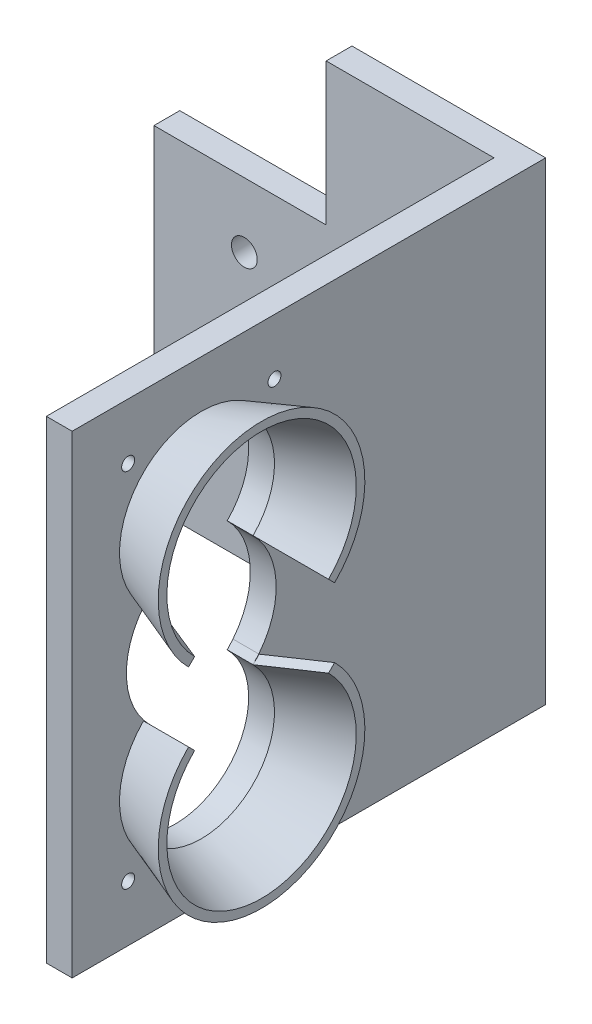
SolidWorks part; units mm, degrees
ref_plane "前视基准面" through (0, 0, 0) normal (0, 0, 1) x (1, 0, 0)
ref_plane "上视基准面" through (0, 0, 0) normal (0, 1, 0) x (1, 0, 0)
ref_plane "右视基准面" through (0, 0, 0) normal (1, 0, 0) x (0, 0, -1)
other "Configuration Table"
sketch "草图1" plane through (0, 0, 0) normal (0, 1, 0) x (1, 0, 0)
  line L0 (-16.6176, 27.2843) -> (25.8824, 27.2843)
  line L1 (25.8824, 27.2843) -> (25.8824, -27.7157)
  line L2 (25.8824, -27.7157) -> (22.8824, -27.7157)
  line L3 (22.8824, -27.7157) -> (22.8824, 24.2843)
  line L4 (22.8824, 24.2843) -> (-16.6176, 24.2843)
  line L5 (-16.6176, 24.2843) -> (-16.6176, 27.2843)
  dimension "D1" = 55
  dimension "D2" = 42.5
  dimension "D3" = 3
  dimension "D4" = 3
extrude "凸台-拉伸1" add sketch "草图1" along normal mid plane 55
ref_plane "基准面1" through (0, 0, -27.2843) normal (0, 0, -1) x (-1, 0, 0)
sketch "草图2" plane through (0, 0, -27.2843) normal (0, 0, -1) x (-1, 0, 0)
  line L0 (4.6176, -3.5) -> (-12.3824, -3.5)
  line L1 (-25.8824, 27.5) -> (-25.8824, -27.5) construction
  line L2 (16.6176, 27.5) -> (16.6176, -27.5) construction
  line L3 (-25.8824, 27.5) -> (16.6176, 27.5) construction
  line L4 (16.6176, -11) -> (-3.3824, -11)
  line L5 (-3.3824, -11) -> (-3.3824, -27.5)
  line L6 (-25.8824, -27.5) -> (16.6176, -27.5) construction
  line L7 (-3.3824, -27.5) -> (16.6176, -27.5)
  line L8 (16.6176, -27.5) -> (16.6176, -11)
  line L9 (-25.8824, 0) -> (16.6176, 0)
  line L10 (-3.3824, 27.5) -> (16.6176, 27.5)
  line L11 (-3.3824, 11) -> (-3.3824, 27.5)
  line L12 (16.6176, 11) -> (-3.3824, 11)
  line L13 (16.6176, 27.5) -> (16.6176, 11)
  circle A2 centre (6.1176, -3.5) radius 1.5
  circle A3 centre (-13.8824, -3.5) radius 1.5
  circle A4 centre (6.1176, 3.5) radius 1.5
  circle A5 centre (-13.8824, 3.5) radius 1.5
  dimension "D3" = 3
  dimension "D4" = 3
  dimension "D1" = 31
  dimension "D2" = 31
  dimension "D5" = 10.5
  dimension "D6" = 12
  dimension "D7" = 7.5
  dimension "D8" = 20
ref_plane "基准面2" through (25.8824, 0, 0) normal (1, 0, 0) x (0, 0, -1)
sketch "草图3" plane through (25.8824, 0, 0) normal (1, 0, 0) x (0, 0, -1)
  line L0 (-27.7157, 27.5) -> (-27.7157, -27.5) construction
  line L1 (-22.7157, 22.5) -> (-2.7157, 22.5)
  line L2 (-22.7157, 22.5) -> (-22.7157, -22.5)
  line L3 (-22.7157, -22.5) -> (-2.7157, -22.5)
  line L4 (-2.7157, 22.5) -> (-2.7157, -22.5)
  line L5 (-22.7157, 22.5) -> (-2.7157, -22.5) construction
  line L6 (-22.7157, -22.5) -> (-2.7157, 22.5) construction
  line L7 (-12.7157, 22.5) -> (-12.7157, 22)
  line L8 (-12.7157, 12.5) -> (-6.7053, 6.4896)
  line L9 (-12.7157, 12.5) -> (-18.7261, 6.4896)
  line L10 (-12.7157, -12.5) -> (-18.7261, -6.4896)
  line L11 (-12.7157, -12.5) -> (-6.7053, -6.4896)
  line L12 (-12.7157, -22) -> (-12.7157, -22.5)
  line L13 (-12.7157, -4) -> (-12.7157, -21)
  line L14 (-12.7157, 3) -> (-12.7157, -3)
  line L15 (-12.7157, 21) -> (-12.7157, 4)
  line L16 (-22.7157, 0) -> (-2.7157, 0)
  line L17 (-18.7261, 6.4896) -> (-19.3945, 5.744)
  line L18 (-6.7053, 6.4896) -> (-6.0369, 5.744)
  line L19 (-6.7053, -6.4896) -> (-6.0369, -5.744)
  line L20 (-18.7261, -6.4896) -> (-19.3945, -5.744)
  circle A0 centre (-12.7157, 12.5) radius 8.5
  circle A1 centre (-12.7157, -12.5) radius 8.5
  arc A2 (-6.0369, 5.744) -> (-6.0369, -5.744) centre (-13.1949, 0) cw
  arc A3 (-19.3945, 5.744) -> (-19.3945, -5.744) centre (-12.2365, 0) ccw
  circle A4 centre (-12.7157, 12.5) radius 9.5
  circle A5 centre (-12.7157, -12.5) radius 9.5
  circle A6 centre (-4.2157, -21) radius 0.75
  circle A7 centre (-21.2157, -21) radius 0.75
  circle A8 centre (-4.2157, 21) radius 0.75
  circle A9 centre (-21.2157, 21) radius 0.75
  point P0 (0, 0)
  dimension "D6" = 17
  dimension "D7" = 17
  dimension "D8" = 19
  dimension "D9" = 19
  dimension "D11" = 1.5
  dimension "D1" = 45
  dimension "D2" = 20
  dimension "D3" = 5
  dimension "D4" = 10
  dimension "D5" = 10
  dimension "D10" = 1.5
  dimension "D12" = 1.5
extrude "切除-拉伸3" cut sketch "草图3" against normal blind 3 contours L8 A0 L15 | L15 A0 L8 | L9 A0 L15 | L15 A0 L9 | A4 L14 L16 A2 | A5 A2 L16 L14 | A4 A3 L16 L14 | A5 L14 L16 A3 | L13 A1 L11 | L11 A1 L13 | L13 A1 L10 | L10 A1 L13 | A7 | A6 | A9 | A8 | L19 A5 L20 A1 | L17 A4 L18 A0
ref_plane "基准面3" through (32.8824, 0, 0) normal (1, 0, 0) x (0, 0, -1)
sketch "草图4" plane through (32.8824, 0, 0) normal (1, 0, 0) x (0, 0, -1)
  circle A0 centre (-12.7157, 12.5) radius 12
  circle A1 centre (-12.7157, 12.5) radius 11
ref_plane "基准面4" through (0, 0, 12.7157) normal (0, 0, 1) x (0, -1, 0)
sketch "草图5" plane through (0, 0, 12.7157) normal (0, 0, 1) x (0, -1, 0)
  line L0 (-3, 25.8824) -> (-22, 25.8824) construction
  line L1 (-0.5, 32.8824) -> (-24.5, 32.8824) construction
  line L2 (-3, 25.8824) -> (-22, 25.8824)
  line L3 (-0.5, 32.8824) -> (-24.5, 32.8824)
  line L4 (-3, 25.8824) -> (-22, 25.8824)
  line L5 (-22, 25.8824) -> (-24.5, 32.8824)
  line L6 (-22, 25.8824) -> (-21, 25.8824)
  line L7 (-21, 25.8824) -> (-23.5, 32.8824)
  line L8 (-23.5, 32.8824) -> (-24.5, 32.8824)
  line L9 (-12.5, 32.8824) -> (-12.5, 25.8824)
  point P4 (-12.5, 32.8824)
  dimension "D1" = 1
revolve "旋转1" add sketch "草图5" angle 135 about L9
mirror "镜向1" about plane through (0, 0, 0) normal (0, 1, 0) of "旋转1"
mirror "镜向2" about plane through (0, 0, 12.7157) normal (0, 0, 1) of "旋转1"
mirror "镜向3" about plane through (0, 0, 12.7157) normal (0, 0, 1) of "镜向1"
extrude "切除-拉伸4" cut sketch "草图2" against normal blind 3 contours L13 L10 L11 L12 | A5 | A4 | L8 L4 L5 L7
